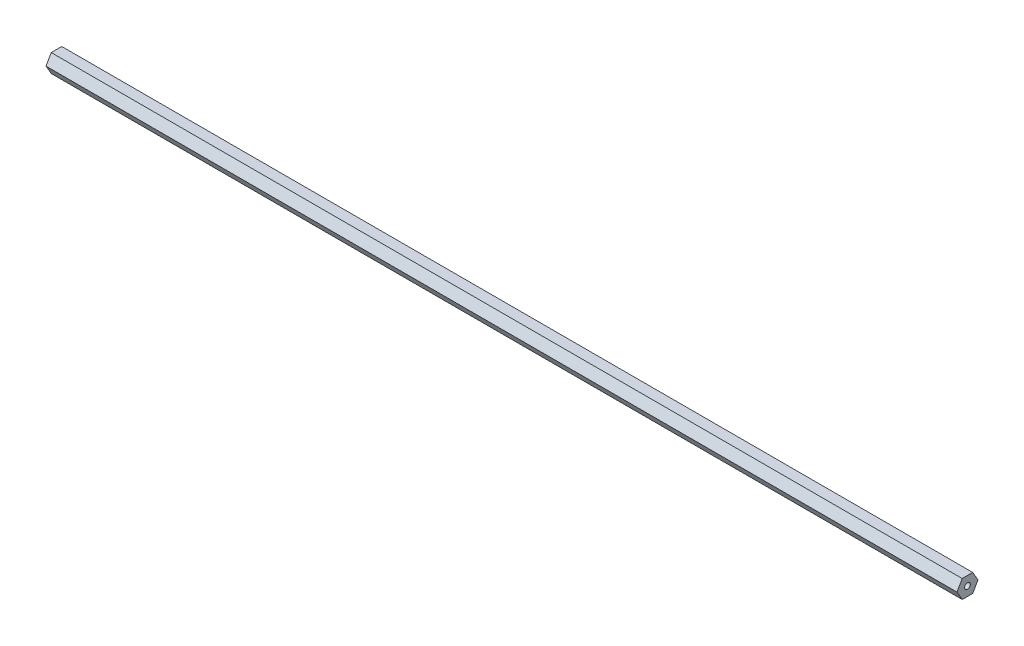
SolidWorks part; units mm, degrees
ref_plane "Front Plane" through (0, 0, 0) normal (0, 0, 1) x (1, 0, 0)
ref_plane "Top Plane" through (0, 0, 0) normal (0, 1, 0) x (1, 0, 0)
ref_plane "Right Plane" through (0, 0, 0) normal (1, 0, 0) x (0, 0, -1)
sketch "Sketch1" plane through (0, 0, 0) normal (1, 0, 0) x (0, 0, -1)
  line L1 (3.65, 6.3593) -> (-3.6823, 6.3407)
  line L2 (-3.6823, 6.3407) -> (-7.3323, -0.0186)
  line L3 (-7.3323, -0.0186) -> (-3.65, -6.3593)
  line L4 (-3.65, -6.3593) -> (3.6823, -6.3407)
  line L5 (3.6823, -6.3407) -> (7.3323, 0.0186)
  line L6 (7.3323, 0.0186) -> (3.65, 6.3593)
  circle A0 centre (0, 0) radius 6.35 construction
  circle A1 centre (0, 0) radius 2.0013
  dimension "D1" = 12.7
extrude "Boss-Extrude1" add sketch "Sketch1" along normal blind 635
